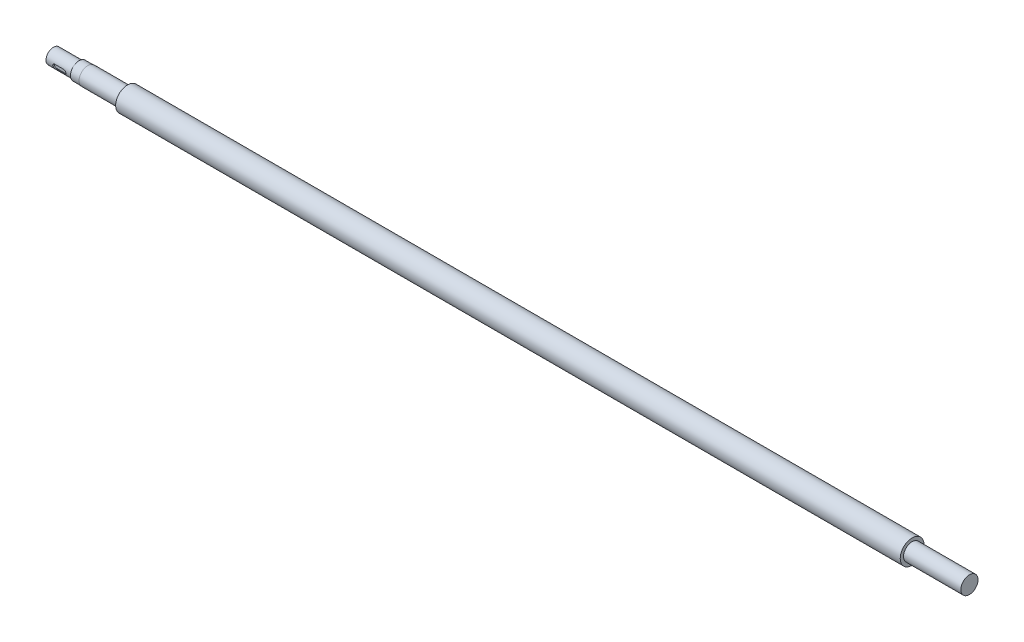
SolidWorks part; units mm, degrees
ref_plane "前视基准面" through (0, 0, 0) normal (0, 0, 1) x (1, 0, 0)
ref_plane "上视基准面" through (0, 0, 0) normal (0, 1, 0) x (1, 0, 0)
ref_plane "右视基准面" through (0, 0, 0) normal (1, 0, 0) x (0, 0, -1)
sketch "草图2" plane through (0, 0, 0) normal (0, 0, 1) x (1, 0, 0)
  line L0 (41.3003, 0) -> (102.9825, 0) construction
  line L1 (0, 0) -> (0, 17)
  line L2 (0, 17) -> (58, 17)
  line L3 (58, 17) -> (58, 19.5)
  line L4 (58, 19.5) -> (78, 19.5)
  line L5 (78, 19.5) -> (78, 20)
  line L6 (78, 20) -> (168, 20)
  line L7 (168, 20) -> (168, 27)
  line L8 (168, 27) -> (1948, 27)
  line L9 (1948, 27) -> (1948, 19.5)
  line L10 (1948, 19.5) -> (2078, 19.5)
  line L11 (2078, 19.5) -> (2078, 0)
  line L12 (0, 0) -> (2078, 0)
  dimension "D1" = 17
  dimension "D2" = 58
  dimension "D3" = 19.5
  dimension "D4" = 20
  dimension "D5" = 20
  dimension "D6" = 90
  dimension "D7" = 1780
  dimension "D8" = 27
  dimension "D9" = 19.5
  dimension "D10" = 130
revolve "旋转5" add sketch "草图2" angle 360 about L0
ref_plane "基准面1" through (0, 0, 17) normal (0, 0, 1) x (1, 0, 0)
sketch "草图3" plane through (0, 0, 17) normal (0, 0, 1) x (1, 0, 0)
  line L0 (20, -3) -> (40, -3) construction
  line L1 (20, 2) -> (40, 2)
  line L2 (20, -8) -> (40, -8)
  line L3 (58, 17) -> (0, 17) construction
  line L4 (0, 17) -> (0, -17) construction
  arc A0 (20, 2) -> (20, -8) centre (20, -3) ccw
  arc A1 (40, -8) -> (40, 2) centre (40, -3) ccw
  point P2 (30, -3)
  dimension "D1" = 10
  dimension "D2" = 20
  dimension "D3" = 15
  dimension "D4" = 20
extrude "切除-拉伸1" cut sketch "草图3" against normal blind 4
